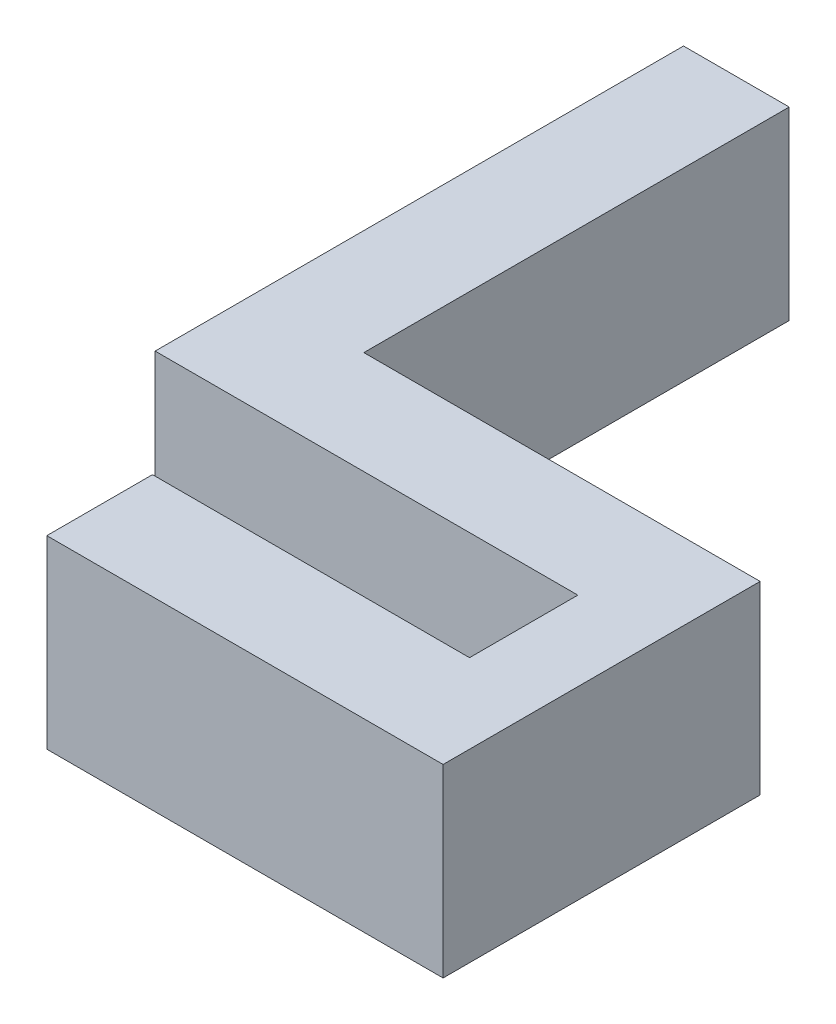
SolidWorks part; units mm, degrees
ref_plane "Front Plane" through (0, 0, 0) normal (0, 0, 1) x (1, 0, 0)
ref_plane "Top Plane" through (0, 0, 0) normal (0, 1, 0) x (1, 0, 0)
ref_plane "Right Plane" through (0, 0, 0) normal (1, 0, 0) x (0, 0, -1)
sketch "Sketch1" plane through (0, 0, 0) normal (0, 1, 0) x (1, 0, 0)
  line L0 (0, 0) -> (12, 0)
  line L1 (12, 0) -> (12, -4.1)
  line L2 (12, -4.1) -> (0, -4.1)
  line L3 (0, -4.1) -> (0, -8.1)
  line L4 (0, -8.1) -> (15, -8.1)
  line L5 (15, -8.1) -> (15, 3.9)
  line L6 (15, 3.9) -> (1.5926, 3.9)
  line L7 (0, 0) -> (-4, 0)
  line L8 (1.5926, 3.9) -> (0, 3.9)
  line L9 (-4, 0) -> (-4, 20)
  line L10 (-4, 20) -> (0, 20)
  line L11 (0, 3.9) -> (0, 20)
  dimension "D1" = 4
  dimension "D2" = 4.1
  dimension "D3" = 12
  dimension "D4" = 3
  dimension "D5" = 3.9
  dimension "D6" = 12
  dimension "D7" = 4
  dimension "D8" = 20
extrude "Boss-Extrude1" add sketch "Sketch1" along normal blind 7
sketch "Sketch2" plane through (0, 0, 0) normal (0, 0, 1) x (1, 0, 0)
  line L1 (12, 0) -> (0, 0)
  line L2 (12, 0) -> (12, 2.6)
  line L3 (12, 2.6) -> (0, 2.6)
  line L4 (0, 0) -> (0, 2.6)
  dimension "D1" = 2.6
extrude "Cut-Extrude1" cut sketch "Sketch2" against normal blind 7
